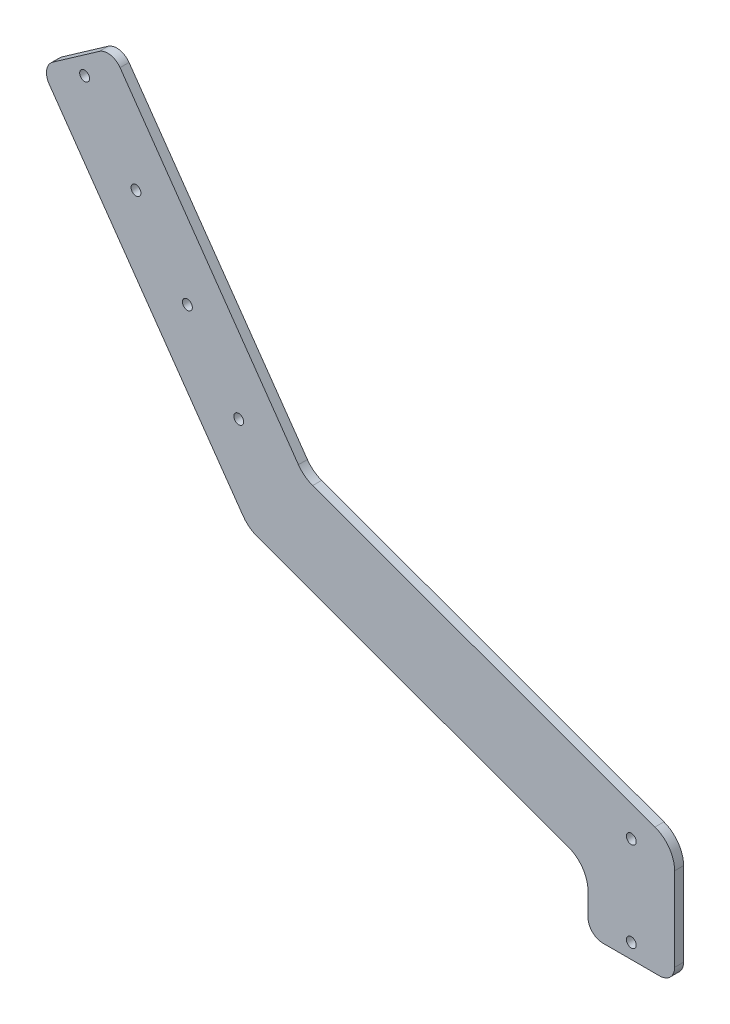
SolidWorks part; units mm, degrees
material "环氧板"
ref_plane "前视基准面" through (0, 0, 0) normal (0, 0, 1) x (1, 0, 0)
ref_plane "上视基准面" through (0, 0, 0) normal (0, 1, 0) x (1, 0, 0)
ref_plane "右视基准面" through (0, 0, 0) normal (1, 0, 0) x (0, 0, -1)
other "Configuration Table"
sketch "草图1" plane through (0, 0, 0) normal (0, 0, 1) x (1, 0, 0)
  line L0 (-183.0527, 159.7346) -> (-71.2052, 0) construction
  line L1 (0, 0) -> (-133.1637, 0) construction
  line L2 (-183.0527, 159.7346) -> (-165.8454, 135.1601) construction
  line L3 (-14.5, -5) -> (14.5, -5)
  line L4 (14.5, -5) -> (14.5, 35)
  line L6 (-174.0428, 172.1473) -> (-197.7982, 155.5136)
  line L7 (-197.7982, 155.5136) -> (-128.1628, 56.0639)
  line L9 (-128.1628, 56.0639) -> (-14.5, 14.694)
  line L10 (-14.5, 14.694) -> (-14.5, -5)
  line L11 (0, 0) -> (0, 61.7369) construction
  line L12 (-174.0428, 172.1473) -> (-109.652, 80.1876)
  line L13 (-109.652, 80.1876) -> (14.5, 35)
  line L14 (-148.6381, 110.5855) -> (-131.4308, 86.011) construction
  circle A0 centre (0, 0) radius 1.65
  circle A1 centre (0, 30) radius 1.65
  circle A2 centre (-183.0527, 159.7346) radius 1.65
  circle A3 centre (-165.8454, 135.1601) radius 1.65
  circle A4 centre (-148.6381, 110.5855) radius 1.65
  circle A5 centre (-85, 0) radius 1.65 construction
  circle A6 centre (-131.4308, 86.011) radius 1.65
  dimension "D1" = 30
  dimension "D2" = 3.3
  dimension "D8" = 5
  dimension "D9" = 85
  dimension "D10" = 5
  dimension "D3" = 55
  dimension "D5" = 30
  dimension "D6" = 29
  dimension "D7" = 29
  dimension "D11" = 11.3
  dimension "D12" = 40
  dimension "D13" = 200
  dimension "D15" = 30
  dimension "D16" = 29
  dimension "D17" = 110
  dimension "D4" = 3
  dimension "D14" = 2
extrude "凸台-拉伸1" add sketch "草图1" along normal blind 3
fillet "圆角1" radius 10 4 edges at (-14.5, 14.694, 1.5) (-109.652, 80.1876, 1.5) (14.5, 35, 1.5) (-128.1628, 56.0639, 1.5)
fillet "圆角2" radius 5 4 edges at (14.5, -5, 1.5) (-14.5, -5, 1.5) (-174.0428, 172.1473, 1.5) (-197.7982, 155.5136, 1.5)
